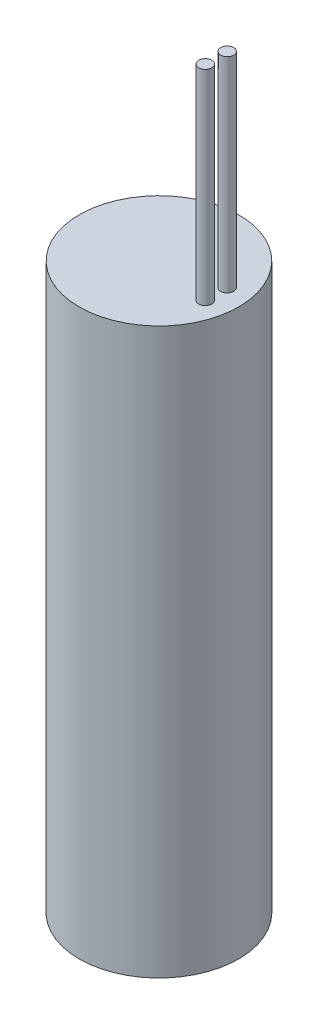
SolidWorks part; units mm, degrees
ref_plane "Front Plane" through (0, 0, 0) normal (0, 0, 1) x (1, 0, 0)
ref_plane "Top Plane" through (0, 0, 0) normal (0, 1, 0) x (1, 0, 0)
ref_plane "Right Plane" through (0, 0, 0) normal (1, 0, 0) x (0, 0, -1)
sketch "Sketch1" plane through (0, 0, 0) normal (0, 1, 0) x (1, 0, 0)
  circle A0 centre (0, 0) radius 9.75
  dimension "D1" = 19.5
extrude "Boss-Extrude1" add sketch "Sketch1" along normal blind 69
sketch "Sketch2" plane through (0, 69, 0) normal (0, 1, 0) x (1, 0, 0)
  line L0 (7, 1.338) -> (7, -1.338) construction
  circle A0 centre (7, 1.338) radius 0.8
  circle A1 centre (7, -1.338) radius 0.8
  point P4 (7, 0)
  dimension "D1" = 1.6
  dimension "D2" = 7
extrude "Boss-Extrude2" add sketch "Sketch2" along normal blind 25
